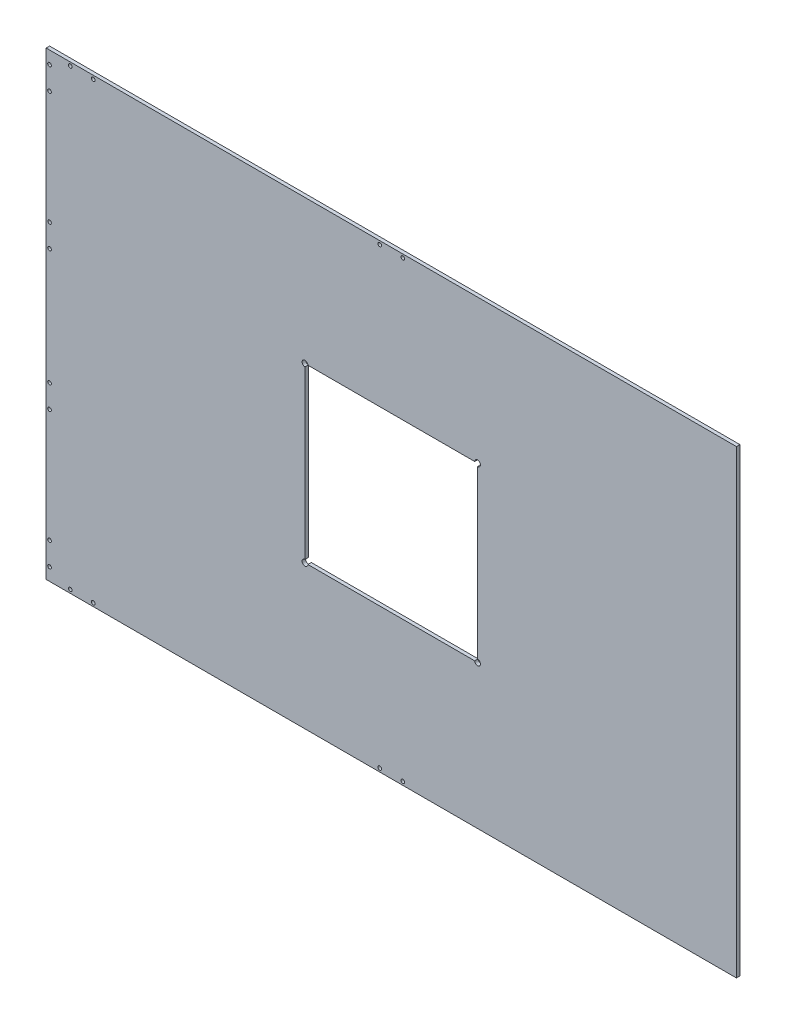
SolidWorks part; units mm, degrees
ref_plane "前视基准面" through (0, 0, 0) normal (0, 0, 1) x (1, 0, 0)
ref_plane "上视基准面" through (0, 0, 0) normal (0, 1, 0) x (1, 0, 0)
ref_plane "右视基准面" through (0, 0, 0) normal (1, 0, 0) x (0, 0, -1)
other "Configuration Table"
sketch "草图1" plane through (0, 0, 0) normal (0, 0, 1) x (1, 0, 0)
  line L1 (-300, 200) -> (300, 200)
  line L2 (-300, 200) -> (-300, -200)
  line L3 (-300, -200) -> (300, -200)
  line L4 (300, 200) -> (300, -200)
  line L5 (-300, 200) -> (300, -200) construction
  line L6 (-300, -200) -> (300, 200) construction
  point P0 (0, 0)
  dimension "D1" = 600
  dimension "D2" = 400
extrude "凸台-拉伸1" add sketch "草图1" along normal blind 3
sketch "草图2" plane through (0, 0, 3) normal (0, 0, 1) x (1, 0, 0)
  line L0 (-300, -200) -> (300, -200) construction
  line L1 (0, 0) -> (0, -324.809) construction
  line L2 (0, 0) -> (136.5757, 0) construction
  circle A2 centre (-10, -197) radius 1.6
  circle A3 centre (10, -197) radius 1.6
  circle A4 centre (10, 197) radius 1.6
  circle A5 centre (-10, 197) radius 1.6
  dimension "D1" = 3.2
  dimension "D2" = 20
  dimension "D3" = 3
  dimension "D4" = 10
extrude "切除-拉伸1" cut sketch "草图2" against normal through all
sketch "草图3" plane through (0, 0, 3) normal (0, 0, 1) x (1, 0, 0)
  line L0 (-300, 200) -> (-300, -200) construction
  line L1 (300, 200) -> (-300, 200) construction
  line L2 (0, 0) -> (-483.5184, 0) construction
  circle A0 centre (-297, 169) radius 1.6
  circle A1 centre (-297, 189) radius 1.6
  circle A2 centre (-279, 197) radius 1.6
  circle A3 centre (-259, 197) radius 1.6
  circle A8 centre (-259, -197) radius 1.6
  circle A9 centre (-279, -197) radius 1.6
  circle A10 centre (-297, -189) radius 1.6
  circle A11 centre (-297, -169) radius 1.6
  dimension "D1" = 3.2
  dimension "D3" = 3
  dimension "D4" = 11
  dimension "D2" = 20
  dimension "D5" = 20
  dimension "D6" = 3
  dimension "D7" = 21
extrude "切除-拉伸2" cut sketch "草图3" against normal through all
sketch "草图4" plane through (0, 0, 0) normal (0, 0, -1) x (-1, 0, 0)
  line L1 (-75, 75) -> (75, 75)
  line L2 (-75, 75) -> (-75, -75)
  line L3 (-75, -75) -> (75, -75)
  line L4 (75, 75) -> (75, -75)
  line L5 (-75, 75) -> (75, -75) construction
  line L6 (-75, -75) -> (75, 75) construction
  point P0 (0, 0)
  dimension "D1" = 150
  dimension "D2" = 150
extrude "切除-拉伸3" cut sketch "草图4" against normal through all
sketch "草图5" plane through (0, 0, 0) normal (0, 0, -1) x (-1, 0, 0)
  circle A0 centre (75, 75) radius 2.5
  circle A1 centre (75, -75) radius 2.5
  circle A2 centre (-75, -75) radius 2.5
  circle A3 centre (-75, 75) radius 2.5
  dimension "D1" = 5
extrude "切除-拉伸4" cut sketch "草图5" against normal through all
sketch "草图6" plane through (0, 0, 0) normal (0, 0, -1) x (-1, 0, 0)
  line L0 (0, 0) -> (425.3024, 0) construction
  line L1 (300, 200) -> (300, -200) construction
  circle A2 centre (297, -50.5) radius 1.575
  circle A3 centre (297, -70.5) radius 1.575
  circle A4 centre (297, 70.5) radius 1.575
  circle A5 centre (297, 50.5) radius 1.575
  point P0 (297, -70.5)
  point P16 (0, 0)
  dimension "D1" = 3.15
  dimension "D2" = 101
  dimension "D3" = 20
  dimension "D4" = 3
extrude "切除-拉伸5" cut sketch "草图6" against normal through all
